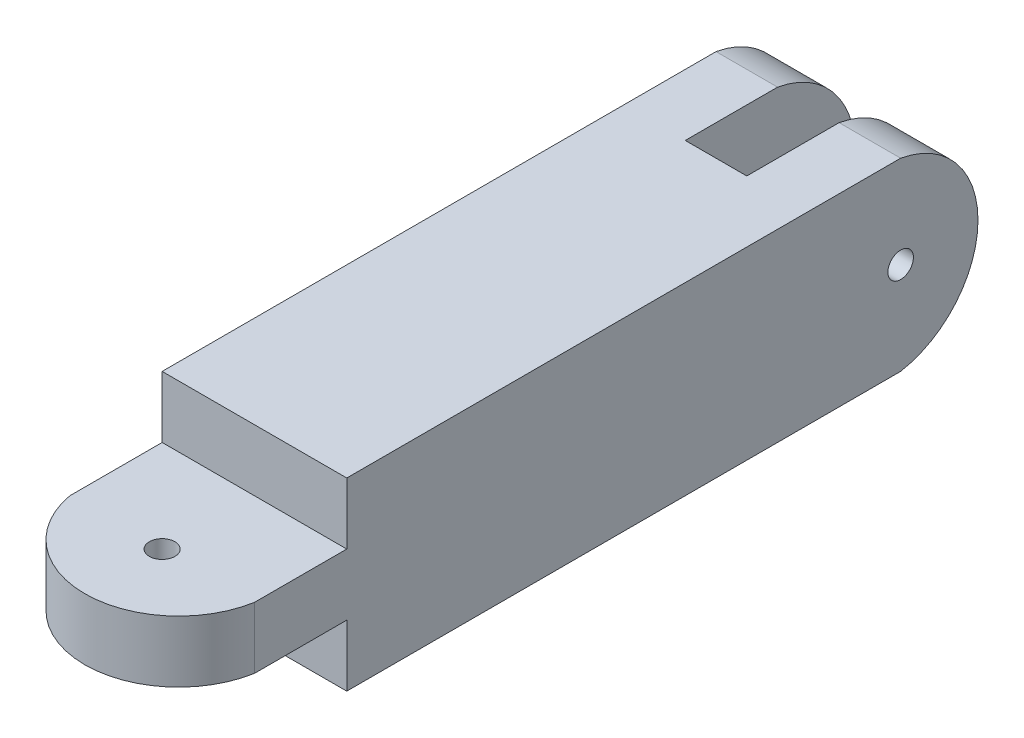
SolidWorks part; units mm, degrees
ref_plane "Front Plane" through (0, 0, 0) normal (0, 0, 1) x (1, 0, 0)
ref_plane "Top Plane" through (0, 0, 0) normal (0, 1, 0) x (1, 0, 0)
ref_plane "Right Plane" through (0, 0, 0) normal (1, 0, 0) x (0, 0, -1)
sketch "Sketch2" plane through (0, 0, 0) normal (0, 0, 1) x (1, 0, 0)
  line L1 (-30, 30) -> (30, 30)
  line L2 (-30, 30) -> (-30, -30)
  line L3 (-30, -30) -> (30, -30)
  line L4 (30, 30) -> (30, -30)
  line L5 (-30, 30) -> (30, -30) construction
  line L6 (-30, -30) -> (30, 30) construction
  point P0 (0, 0)
  dimension "D1" = 60
  dimension "D2" = 60
extrude "Boss-Extrude1" add sketch "Sketch2" along normal blind 150
ref_plane "Plane1" through (0, 0, 0) normal (0, 0, -1) x (-1, 0, 0)
sketch "Sketch3" plane through (0, 0, 0) normal (0, 0, -1) x (-1, 0, 0)
  line L0 (-30, 30) -> (30, 30) construction
  line L1 (30, -30) -> (10, -30)
  line L2 (30, -30) -> (30, 30)
  line L3 (30, 30) -> (10, 30)
  line L4 (10, -30) -> (10, 30)
  line L5 (30, -30) -> (-30, -30) construction
  line L6 (-30, 30) -> (-10, 30)
  line L7 (-30, 30) -> (-30, -30)
  line L8 (-30, -30) -> (-10, -30)
  line L9 (-10, 30) -> (-10, -30)
  dimension "D1" = 20
  dimension "D2" = 20
extrude "Boss-Extrude2" add sketch "Sketch3" along normal blind 30
ref_plane "Plane2" through (30, 0, 0) normal (1, 0, 0) x (0, 0, -1)
sketch "Sketch4" plane through (30, 0, 0) normal (1, 0, 0) x (0, 0, -1)
  line L0 (30, 30) -> (30, -30)
  arc A0 (30, 30) -> (30, -30) centre (24.6689, 0) cw
  dimension "D1" = 30.47
extrude "Boss-Extrude3" add sketch "Sketch4" against normal blind 20
ref_plane "Plane3" through (-30, 0, 0) normal (-1, 0, 0) x (0, 0, 1)
sketch "Sketch5" plane through (-30, 0, 0) normal (-1, 0, 0) x (0, 0, 1)
  line L0 (-30, -30) -> (-30, 30)
  arc A0 (-30, -30) -> (-30, 30) centre (-24.6689, 0) cw
  dimension "D1" = 30.47
extrude "Boss-Extrude4" add sketch "Sketch5" against normal blind 20
ref_plane "Plane4" through (0, 0, 150) normal (0, 0, 1) x (1, 0, 0)
sketch "Sketch6" plane through (0, 0, 150) normal (0, 0, 1) x (1, 0, 0)
  line L0 (30, -30) -> (30, 30) construction
  line L1 (-30, 10) -> (30, 10)
  line L2 (-30, 10) -> (-30, -10)
  line L3 (-30, -10) -> (30, -10)
  line L4 (30, 10) -> (30, -10)
  line L5 (-30, 10) -> (30, -10) construction
  line L6 (-30, -10) -> (30, 10) construction
  point P0 (0, 0)
  dimension "D1" = 20
extrude "Boss-Extrude5" add sketch "Sketch6" along normal blind 30
ref_plane "Plane5" through (0, 10, 0) normal (0, 1, 0) x (1, 0, 0)
sketch "Sketch7" plane through (0, 10, 0) normal (0, 1, 0) x (1, 0, 0)
  line L0 (30, -180) -> (-30, -180)
  arc A0 (30, -180) -> (-30, -180) centre (0, -174.6689) cw
  dimension "D1" = 30.47
extrude "Boss-Extrude6" add sketch "Sketch7" against normal blind 20
ref_plane "Plane6" through (0, 0, 150) normal (0, 0, 1) x (1, 0, 0)
sketch "Sketch8" plane through (0, 0, 150) normal (0, 0, 1) x (1, 0, 0)
  line L1 (-25.25, -25.25) -> (25.25, -25.25)
  line L2 (-25.25, -25.25) -> (-25.25, 25.25)
  line L3 (-25.25, 25.25) -> (25.25, 25.25)
  line L4 (25.25, -25.25) -> (25.25, 25.25)
  line L5 (-25.25, -25.25) -> (25.25, 25.25) construction
  line L6 (-25.25, 25.25) -> (25.25, -25.25) construction
  point P0 (0, 0)
  dimension "D1" = 50.5
  dimension "D2" = 50.5
extrude "Cut-Extrude2" cut sketch "Sketch8" against normal blind 130 and the other way blind 5 from offset 10 contours L3 L4 L1 L2 offset against normal yes
ref_plane "Plane7" through (0, -10, 0) normal (0, -1, 0) x (-1, 0, 0)
sketch "Sketch9" plane through (0, -10, 0) normal (0, -1, 0) x (-1, 0, 0)
  line L0 (30, -150) -> (-30, -150) construction
  circle A0 centre (0, -180) radius 4.15
  dimension "D1" = 8.3
  dimension "D2" = 30
extrude "Cut-Extrude3" cut sketch "Sketch9" against normal blind 130
ref_plane "Plane8" through (30, 0, 0) normal (1, 0, 0) x (0, 0, -1)
ref_plane "Plane9" through (10, 0, 0) normal (-1, 0, 0) x (0, 0, 1)
sketch "Sketch11" plane through (10, 0, 0) normal (-1, 0, 0) x (0, 0, 1)
  line L0 (0, -30) -> (0, 30) construction
  circle A0 centre (-30, 0) radius 4.15
  dimension "D2" = 8.3
  dimension "D1" = 30
extrude "Cut-Extrude4" cut sketch "Sketch11" against normal through all
ref_plane "Plane10" through (-10, 0, 0) normal (1, 0, 0) x (0, 0, -1)
sketch "Sketch12" plane through (-10, 0, 0) normal (1, 0, 0) x (0, 0, -1)
  line L0 (0, 30) -> (0, -30) construction
  circle A0 centre (30, 0) radius 4.15
  dimension "D1" = 30
  dimension "D2" = 8.3
extrude "Cut-Extrude5" cut sketch "Sketch12" against normal through all
